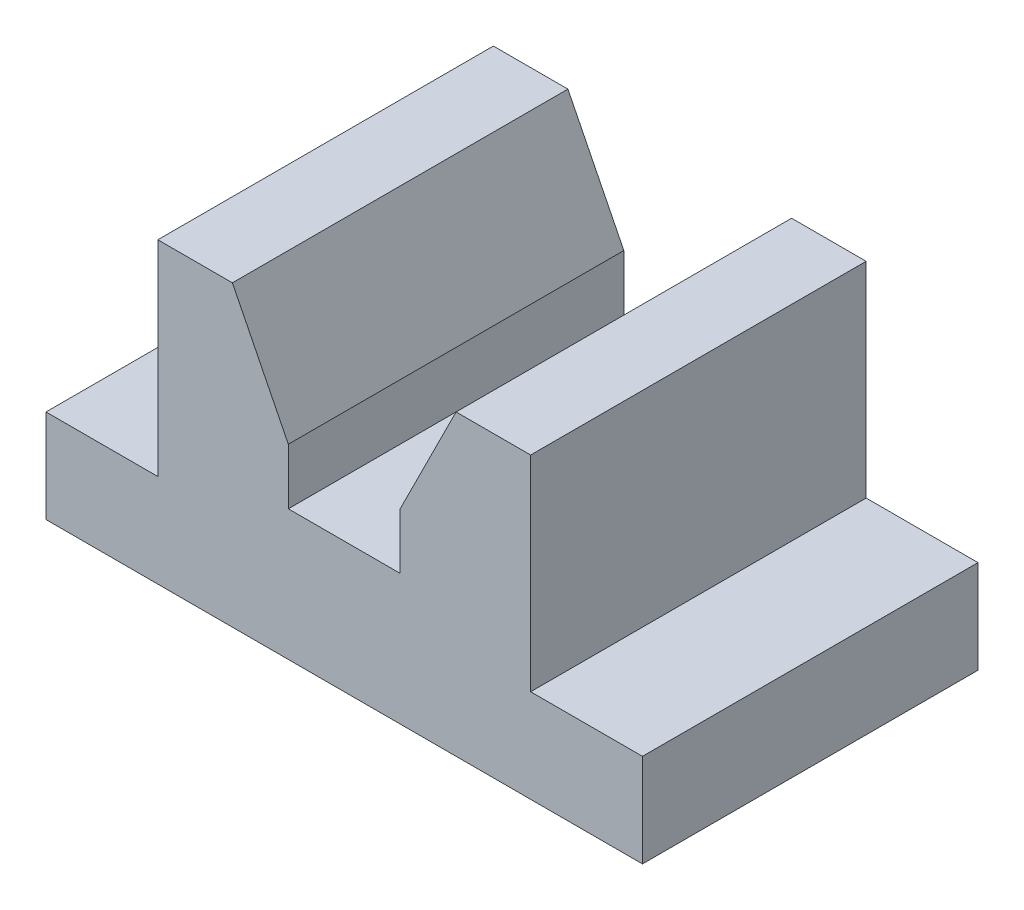
SolidWorks part; units mm, degrees
ref_plane "前视基准面" through (0, 0, 0) normal (0, 0, 1) x (1, 0, 0)
ref_plane "上视基准面" through (0, 0, 0) normal (0, 1, 0) x (1, 0, 0)
ref_plane "右视基准面" through (0, 0, 0) normal (1, 0, 0) x (0, 0, -1)
other "Configuration Table"
sketch "草图1" plane through (0, 0, 0) normal (0, 0, 1) x (1, 0, 0)
  line L0 (0, -522.4849) -> (0, 25601.7621) construction
  line L1 (16, 0) -> (-16, 0)
  line L2 (-16, 0) -> (-16, 5)
  line L3 (-16, 5) -> (-10, 5)
  line L4 (-10, 5) -> (-10, 16)
  line L5 (-10, 16) -> (-6, 16)
  line L6 (-6, 16) -> (-3, 10)
  line L7 (-3, 10) -> (-3, 7)
  line L8 (-3, 7) -> (3, 7)
  line L9 (3, 10) -> (3, 7)
  line L10 (6, 16) -> (3, 10)
  line L11 (10, 16) -> (6, 16)
  line L12 (10, 5) -> (10, 16)
  line L13 (16, 5) -> (10, 5)
  line L14 (16, 0) -> (16, 5)
  point P13 (0, 7)
  point P19 (0, 0)
  dimension "D1" = 20
  dimension "D2" = 12
  dimension "D3" = 6
  dimension "D4" = 9
  dimension "D5" = 6
  dimension "D6" = 16
  dimension "D7" = 5
  dimension "D8" = 32
extrude "凸台-拉伸1" add sketch "草图1" along normal blind 18
